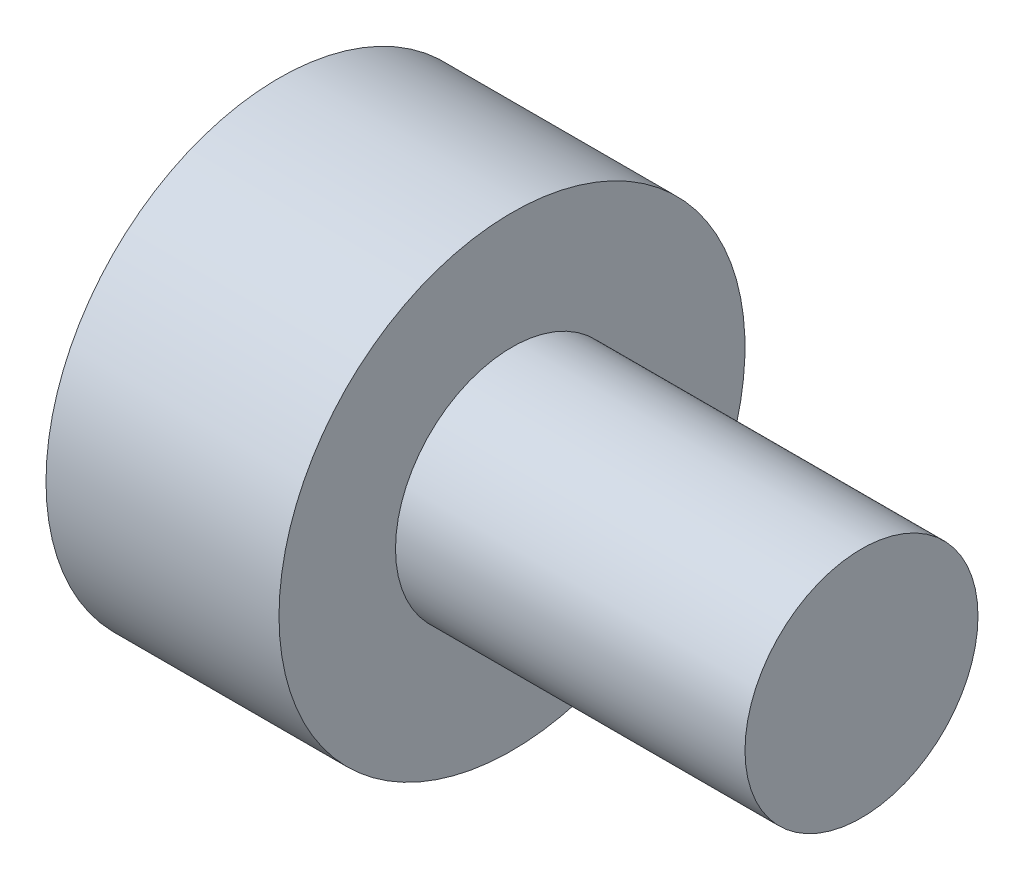
SolidWorks part; units mm, degrees
ref_plane "Plan de face" through (0, 0, 0) normal (0, 0, 1) x (1, 0, 0)
ref_plane "Plan de dessus" through (0, 0, 0) normal (0, 1, 0) x (1, 0, 0)
ref_plane "Plan de droite" through (0, 0, 0) normal (1, 0, 0) x (0, 0, -1)
sketch "Esquisse1" plane through (0, 0, 0) normal (0, 0, 1) x (1, 0, 0)
  line L0 (0, 0) -> (64.218, 0) construction
  line L1 (50, 10) -> (20, 10)
  line L2 (20, 10) -> (20, 20)
  line L3 (20, 20) -> (0, 20)
  line L4 (0, 20) -> (0, 0)
  line L5 (50, 10) -> (50, 0)
  line L6 (0, 0) -> (50, 0)
  dimension "D1" = 50
  dimension "D2" = 20
  dimension "D3" = 10
  dimension "D4" = 20
revolve "Révolution1" add sketch "Esquisse1" angle 360 about L0
